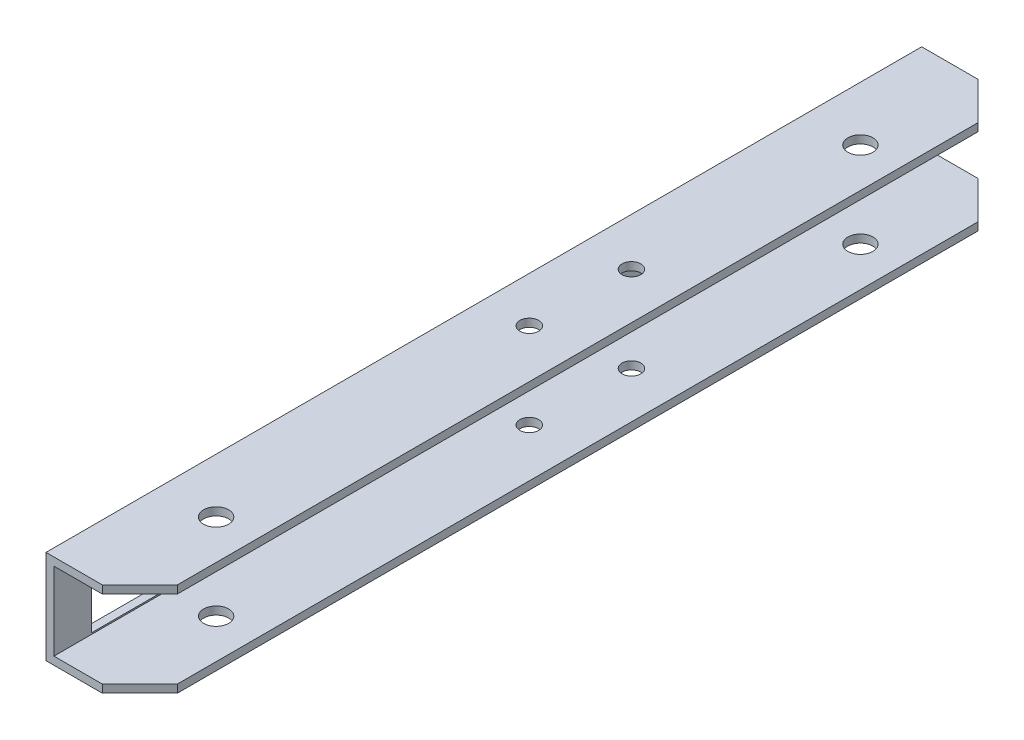
SolidWorks part; units mm, degrees
ref_plane "Front Plane" through (0, 0, 0) normal (0, 0, 1) x (1, 0, 0)
ref_plane "Top Plane" through (0, 0, 0) normal (0, 1, 0) x (1, 0, 0)
ref_plane "Right Plane" through (0, 0, 0) normal (1, 0, 0) x (0, 0, -1)
sketch "Sketch1" plane through (0, 0, 0) normal (0, 0, 1) x (1, 0, 0)
  line L0 (0, -37.5) -> (0, 37.5)
  line L1 (0, 37.5) -> (75, 37.5)
  line L2 (75, 37.5) -> (75, 31.15)
  line L3 (75, 31.15) -> (6.35, 31.15)
  line L4 (6.35, 31.15) -> (6.35, -31.15)
  line L5 (6.35, -31.15) -> (75, -31.15)
  line L6 (75, -31.15) -> (75, -37.5)
  line L7 (75, -37.5) -> (0, -37.5)
  line L8 (0, 0) -> (6.35, 0) construction
  dimension "D1" = 75
  dimension "D2" = 75
  dimension "D3" = 6.35
extrude "Boss-Extrude1" add sketch "Sketch1" along normal blind 700
sketch "Sketch3" plane through (0, 0, 0) normal (-1, 0, 0) x (0, 0, 1)
  line L0 (30, -30) -> (155, -30)
  line L1 (30, -30) -> (30, 30)
  line L2 (155, -30) -> (155, 30)
  line L3 (30, 30) -> (155, 30)
  line L4 (30, -30) -> (155, 30) construction
  line L5 (155, -30) -> (30, 30) construction
  line L6 (350, -37.5) -> (350, 96.3047) construction
  line L7 (700, -37.5) -> (0, -37.5) construction
  line L8 (0, 0) -> (92.5, 0) construction
  line L9 (670, -30) -> (545, -30)
  line L10 (545, -30) -> (545, 30)
  line L11 (670, 30) -> (545, 30)
  line L12 (670, -30) -> (670, 30)
  line L13 (700, 37.5) -> (700, -37.5) construction
  line L14 (400, 10.3833) -> (373, 10.3833)
  line L15 (400, 10.3833) -> (400, -10.3833)
  line L16 (300, 10.3833) -> (300, -10.3833) construction
  line L17 (400, -10.3833) -> (393, -10.3833)
  line L18 (400, 10.3833) -> (300, -10.3833) construction
  line L19 (300, 10.3833) -> (400, -10.3833) construction
  line L20 (307, 10.3833) -> (300, 10.3833)
  line L21 (373, -10.3833) -> (373, -31.15) construction
  line L22 (373, -31.15) -> (327, -31.15)
  line L23 (327, -31.15) -> (327, -10.3833)
  line L24 (373, 31.15) -> (327, 31.15)
  line L25 (373, 31.15) -> (373, 10.3833)
  line L26 (327, 31.15) -> (327, 10.3833) construction
  line L27 (700, -31.15) -> (0, -31.15) construction
  line L28 (373, 31.15) -> (327, 10.3833) construction
  line L29 (327, 31.15) -> (373, 10.3833) construction
  line L30 (327, 31.15) -> (307, 31.15)
  line L31 (327, -10.3833) -> (300, -10.3833)
  line L32 (300, 10.3833) -> (270, 10.3833)
  line L33 (270, 10.3833) -> (270, -10.3833)
  line L34 (270, -10.3833) -> (300, -10.3833)
  line L35 (700, 31.15) -> (0, 31.15) construction
  line L36 (307, 31.15) -> (307, 10.3833)
  line L37 (373, -31.15) -> (393, -31.15)
  line L38 (393, -31.15) -> (393, -10.3833)
  point P1 (92.5, 0)
  point P19 (350, 0)
  point P28 (350, 20.7667)
  dimension "D1" = 60
  dimension "D2" = 30
  dimension "D3" = 125
  dimension "D4" = 20
  dimension "D5" = 100
  dimension "D6" = 46
  dimension "D9" = 30
extrude "Cut-Extrude1" cut sketch "Sketch3" against normal through all
chamfer "Chamfer1" distance 30 angle 45 4 edges at (75, 34.325, 700) (75, -34.325, 700) (75, -34.325, 0) (75, 34.325, 0)
sketch "Sketch4" plane through (0, 37.5, 0) normal (0, 1, 0) x (1, 0, 0)
  line L0 (75, -607.5) -> (43.5, -607.5) construction
  line L1 (75, -670) -> (75, -30) construction
  line L2 (0, -670) -> (0, -545) construction
  line L4 (0, -549.5) -> (0, -665.5) construction
  line L5 (0, -700) -> (0, 0) construction
  line L6 (0, -607.5) -> (43.5, -607.5) construction
  line L7 (0, -350) -> (49.4239, -350) construction
  circle A0 centre (43.5, -607.5) radius 10
  circle A1 centre (43.5, -607.5) radius 62.5 construction
  circle A2 centre (43.5, -607.5) radius 72.5 construction
  circle A3 centre (43.5, -92.5) radius 10
  dimension "D1" = 20
  dimension "D2" = 125
  dimension "D3" = 145
  dimension "D4" = 116
  dimension "D5" = 31.5
extrude "Cut-Extrude2" cut sketch "Sketch4" against normal through all
sketch "Sketch5" plane through (0, -37.5, 0) normal (0, -1, 0) x (1, 0, 0)
  line L1 (0, 350) -> (36.323, 350) construction
  line L6 (75, 670) -> (75, 30) construction
  line L7 (43.5, 607.5) -> (36.323, 350) construction
  line L8 (36.323, 350) -> (43.5, 92.5) construction
  line L11 (0, 700) -> (0, 0) construction
  circle A0 centre (38, 270.0176) radius 7.5
  circle A2 centre (36.323, 350) radius 7.5
  point P10 (43.5, 92.5)
  point P11 (43.5, 607.5)
  dimension "D1" = 15
  dimension "D2" = 37
  dimension "D3" = 80
  dimension "D4" = 36.323
  dimension "D5" = 257.6
extrude "Cut-Extrude3" cut sketch "Sketch5" against normal through all
chamfer "Chamfer2" distance 3 angle 45 7 edges at (0, -20.7667, 393) (0, 20.7667, 307) (6.35, 0, 270) (6.35, 20.7667, 373) (6.35, -20.7667, 327) (6.35, 0, 545) (6.35, 0, 155)
fillet "Fillet1" radius 3 8 edges at (1.675, 31.15, 373) (3.175, 10.3833, 400) (3.175, -10.3833, 400) (1.675, -31.15, 327) (1.675, -10.3833, 270) (1.675, 10.3833, 270) (4.675, -31.15, 393) (4.675, 31.15, 307)
